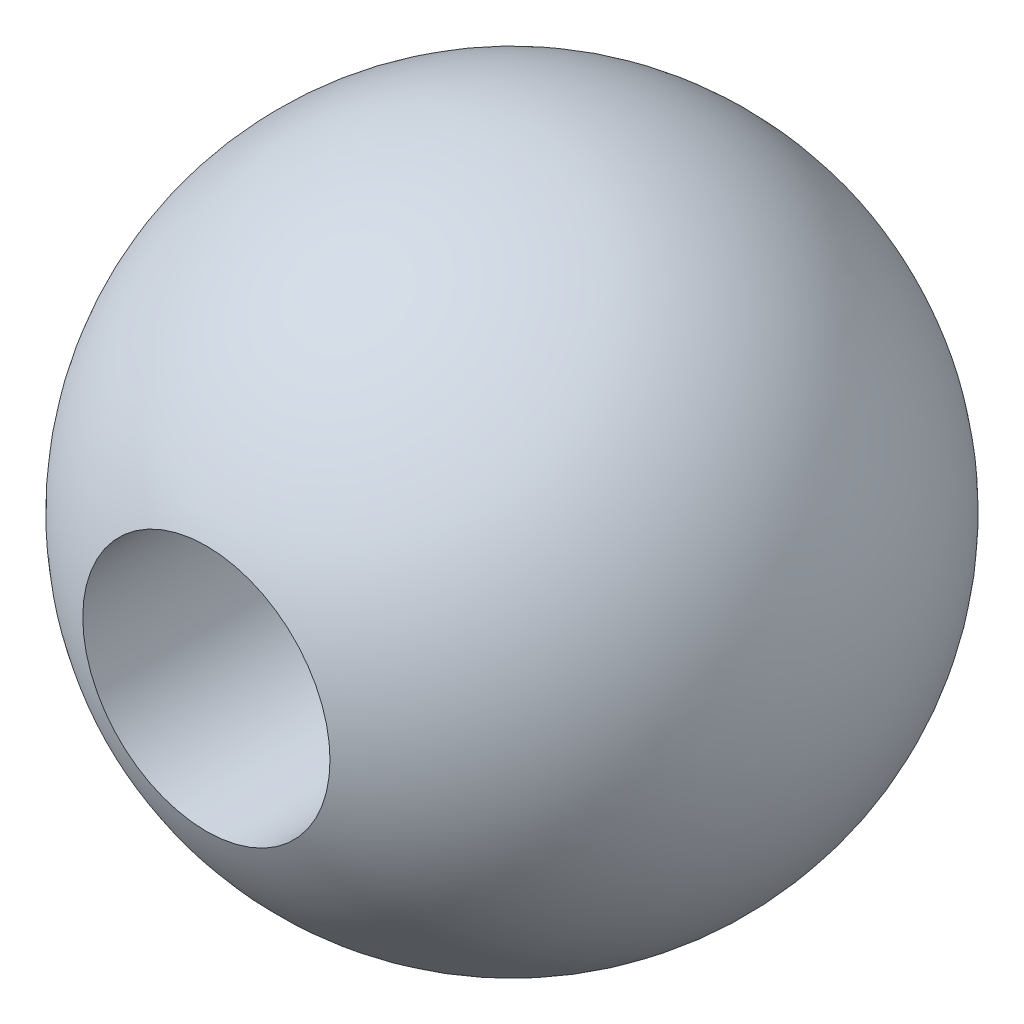
SolidWorks part; units mm, degrees
ref_plane "Front Plane" through (0, 0, 0) normal (0, 0, 1) x (1, 0, 0)
ref_plane "Top Plane" through (0, 0, 0) normal (0, 1, 0) x (1, 0, 0)
ref_plane "Right Plane" through (0, 0, 0) normal (1, 0, 0) x (0, 0, -1)
sketch "Sketch1" plane through (0, 0, 0) normal (0, 0, 1) x (1, 0, 0)
  line L0 (0, 25.4) -> (0, -25.4)
  arc A0 (0, 25.4) -> (0, -25.4) centre (0, 0) cw
  dimension "D1" = 25.4
revolve "Revolve1" add sketch "Sketch1" angle 360 about L0
ref_plane "Plane1" through (0, 0, 25.4) normal (0, 0, 1) x (1, 0, 0)
sketch "Sketch2" plane through (0, 0, 25.4) normal (0, 0, 1) x (1, 0, 0)
  circle A0 centre (0, 0) radius 9.525
  dimension "D1" = 19.05
extrude "Cut-Extrude1" cut sketch "Sketch2" against normal blind 19.05
